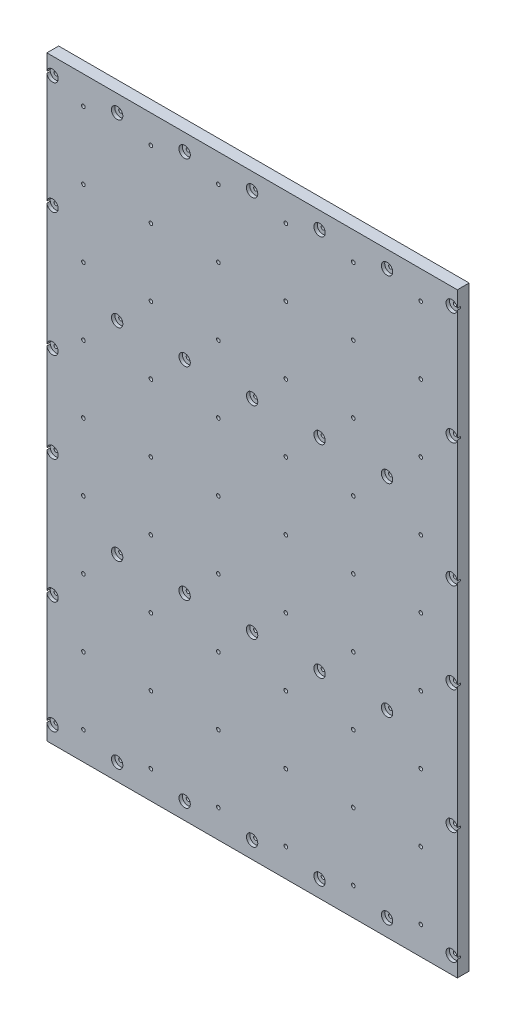
SolidWorks part; units mm, degrees
material "Buche"
ref_plane "Ebene vorne" through (0, 0, 0) normal (0, 0, 1) x (1, 0, 0)
ref_plane "Ebene oben" through (0, 0, 0) normal (0, 1, 0) x (1, 0, 0)
ref_plane "Ebene rechts" through (0, 0, 0) normal (1, 0, 0) x (0, 0, -1)
sketch "Skizze1" plane through (0, 0, 0) normal (0, 0, 1) x (1, 0, 0)
  line L1 (365, 530) -> (-365, 530)
  line L2 (365, 530) -> (365, -530)
  line L3 (365, -530) -> (-365, -530)
  line L4 (-365, 530) -> (-365, -530)
  line L5 (365, 530) -> (-365, -530) construction
  line L6 (365, -530) -> (-365, 530) construction
  point P0 (0, 0)
  dimension "D1" = 730
  dimension "D2" = 1060
extrude "Aufsatz-Linear austragen1" add sketch "Skizze1" along normal blind 21
sketch "Skizze2" plane through (0, 0, 0) normal (0, 0, -1) x (-1, 0, 0)
  line L0 (0, 0) -> (0, -573.4125) construction
  circle A0 centre (60, -480) radius 3.25
  dimension "D3" = 6.5
  dimension "D1" = 480
  dimension "D2" = 60
extrude "Schnitt-Linear austragen1" cut sketch "Skizze2" against normal blind 40
sketch "Skizze3" plane through (0, 0, 0) normal (0, 0, -1) x (-1, 0, 0)
  circle A0 centre (60, -480) radius 10
  dimension "D1" = 20
extrude "Schnitt-Linear austragen2" cut sketch "Skizze3" against normal blind 5
pattern_linear "Lineares Muster1" count 9 spacing 120 along (0, 1, 0) count 3 spacing 120 along (-1, 0, 0) of "Schnitt-Linear austragen1", "Schnitt-Linear austragen2"
mirror "Spiegeln1" about plane through (0, 0, 0) normal (1, 0, 0) of "Schnitt-Linear austragen1", "Lineares Muster1", "Schnitt-Linear austragen2"
sketch "Skizze4" plane through (0, 0, 21) normal (0, 0, 1) x (1, 0, 0)
  line L0 (0, 0) -> (438.8296, 0) construction
  line L1 (0, 0) -> (0, -564.4828) construction
  line L2 (0, -500) -> (400.6412, -500) construction
  line L3 (-365, -530) -> (365, -530) construction
  line L4 (355, -500) -> (355, 0) construction
  line L5 (365, -530) -> (365, 530) construction
  line L6 (-17.7478, -180) -> (300, -180) construction
  line L7 (120, -500) -> (120, -180) construction
  line L8 (240, -500) -> (240, -180) construction
  line L9 (300, -120) -> (300, -240) construction
  circle A0 centre (0, -500) radius 3.25
  circle A1 centre (120, -500) radius 3.25
  circle A2 centre (240, -500) radius 3.25
  circle A3 centre (-120, -500) radius 3.25
  circle A4 centre (-240, -500) radius 3.25
  circle A5 centre (355, -500) radius 3.25
  circle A6 centre (355, -300) radius 3.25
  circle A7 centre (355, -80) radius 3.25
  circle A8 centre (-355, -80) radius 3.25
  circle A9 centre (-355, -300) radius 3.25
  circle A10 centre (-355, -500) radius 3.25
  circle A11 centre (355, 80) radius 3.25
  circle A12 centre (355, 300) radius 3.25
  circle A13 centre (355, 500) radius 3.25
  circle A14 centre (240, 500) radius 3.25
  circle A15 centre (120, 500) radius 3.25
  circle A16 centre (0, 500) radius 3.25
  circle A17 centre (-355, 500) radius 3.25
  circle A18 centre (-355, 300) radius 3.25
  circle A19 centre (-355, 80) radius 3.25
  circle A20 centre (-240, 500) radius 3.25
  circle A21 centre (-120, 500) radius 3.25
  circle A23 centre (120, -180) radius 3.25
  circle A24 centre (240, -180) radius 3.25
  circle A25 centre (0, -180) radius 3.25
  circle A26 centre (-120, -180) radius 3.25
  circle A27 centre (-240, -180) radius 3.25
  circle A28 centre (240, 180) radius 3.25
  circle A29 centre (120, 180) radius 3.25
  circle A30 centre (0, 180) radius 3.25
  circle A31 centre (-120, 180) radius 3.25
  circle A32 centre (-240, 180) radius 3.25
  point P66 (311.2818, -190)
  point P67 (300, -180)
  dimension "D2" = 6.5
  dimension "D3" = 120
  dimension "D4" = 120
  dimension "D6" = 200
  dimension "D7" = 220
  dimension "D1" = 30
  dimension "D5" = 10
extrude "Schnitt-Linear austragen3" cut sketch "Skizze4" against normal blind 50
sketch "Skizze5" plane through (0, 0, 21) normal (0, 0, 1) x (1, 0, 0)
  line L0 (0, 0) -> (0, -591.5839) construction
  line L1 (0, 0) -> (423.9992, 0) construction
  circle A0 centre (355, -500) radius 10.1
  circle A1 centre (240, -500) radius 10.1
  circle A2 centre (120, -500) radius 10.1
  circle A3 centre (0, -500) radius 10.1
  circle A4 centre (-355, -500) radius 10.1
  circle A5 centre (-240, -500) radius 10.1
  circle A6 centre (-120, -500) radius 10.1
  circle A7 centre (240, -180) radius 10.1
  circle A8 centre (120, -180) radius 10.1
  circle A9 centre (0, -180) radius 10.1
  circle A10 centre (355, -300) radius 10.1
  circle A11 centre (355, -80) radius 10.1
  circle A12 centre (-355, -300) radius 10.1
  circle A13 centre (-355, -80) radius 10.1
  circle A14 centre (-240, -180) radius 10.1
  circle A15 centre (-120, -180) radius 10.1
  circle A16 centre (-120, 180) radius 10.1
  circle A17 centre (-240, 180) radius 10.1
  circle A18 centre (-355, 80) radius 10.1
  circle A19 centre (-355, 300) radius 10.1
  circle A20 centre (355, 80) radius 10.1
  circle A21 centre (355, 300) radius 10.1
  circle A22 centre (0, 180) radius 10.1
  circle A23 centre (120, 180) radius 10.1
  circle A24 centre (240, 180) radius 10.1
  circle A25 centre (-120, 500) radius 10.1
  circle A26 centre (-240, 500) radius 10.1
  circle A27 centre (-355, 500) radius 10.1
  circle A28 centre (0, 500) radius 10.1
  circle A29 centre (120, 500) radius 10.1
  circle A30 centre (240, 500) radius 10.1
  circle A31 centre (355, 500) radius 10.1
  dimension "D1" = 20.2
extrude "Schnitt-Linear austragen6" cut sketch "Skizze5" against normal blind 6
